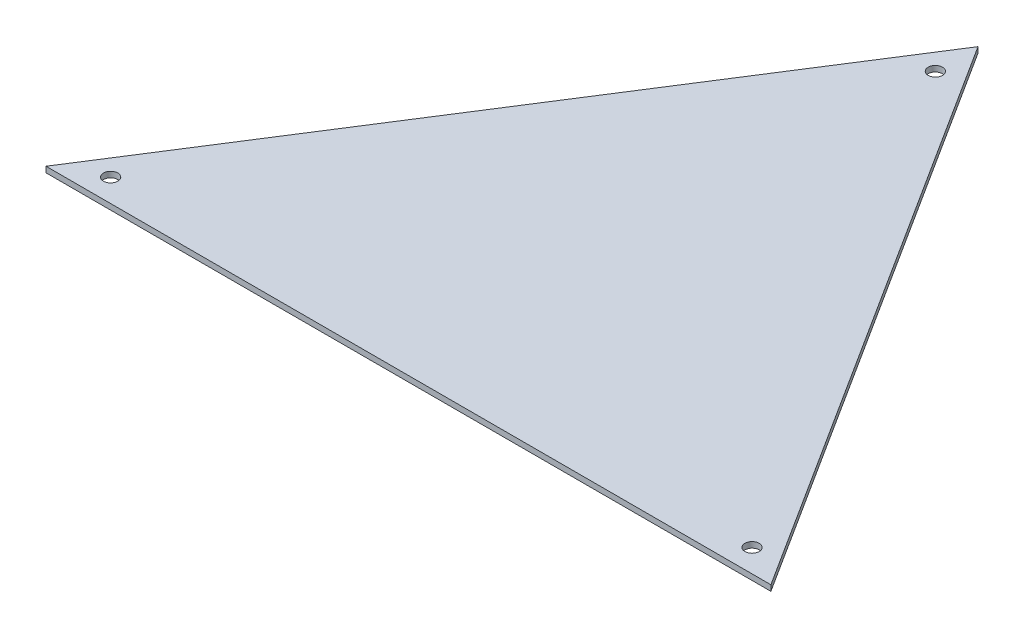
SolidWorks part; units mm, degrees
material "6063-O"
ref_plane "Front Plane" through (0, 0, 0) normal (0, 0, 1) x (1, 0, 0)
ref_plane "Top Plane" through (0, 0, 0) normal (0, 1, 0) x (1, 0, 0)
ref_plane "Right Plane" through (0, 0, 0) normal (1, 0, 0) x (0, 0, -1)
sketch "Sketch1" plane through (0, 0, 0) normal (0, 1, 0) x (1, 0, 0)
  line L0 (0, 303.0554) -> (-200.9352, -12.7)
  line L1 (-200.9352, -12.7) -> (200.9352, -12.7)
  line L2 (200.9352, -12.7) -> (0, 303.0554)
  line L3 (-1.7463, 0) -> (1.7463, 0) construction
  line L4 (0, -1.7463) -> (0, 1.7463) construction
  circle A0 centre (-177.8, 0) radius 3.9687
  circle A1 centre (0, 279.4) radius 3.9688
  circle A2 centre (177.8, 0) radius 3.9687
  dimension "D4" = 7.9375
  dimension "D1" = 279.4
  dimension "D2" = 177.8
  dimension "D3" = 177.8
  dimension "D5" = 12.7
  dimension "D6" = 12.7
  dimension "D7" = 12.7
  dimension "D8" = 12.7
  dimension "D9" = 12.7
extrude "Boss-Extrude1" add sketch "Sketch1" along normal mid plane 3.175
